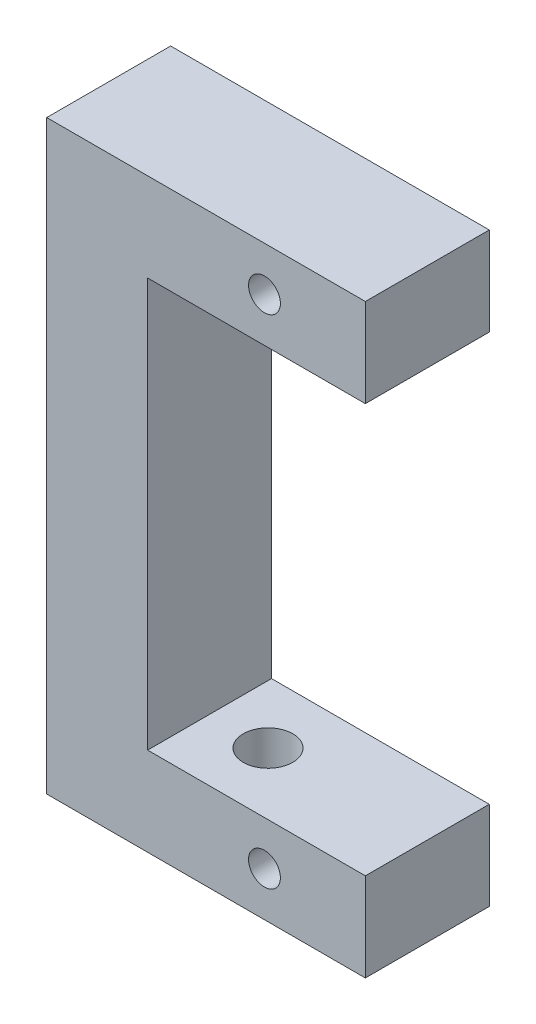
SolidWorks part; units mm, degrees
ref_plane "Front Plane" through (0, 0, 0) normal (0, 0, 1) x (1, 0, 0)
ref_plane "Top Plane" through (0, 0, 0) normal (0, 1, 0) x (1, 0, 0)
ref_plane "Right Plane" through (0, 0, 0) normal (1, 0, 0) x (0, 0, -1)
sketch "Schizzo1" plane through (0, 0, 0) normal (0, 0, 1) x (1, 0, 0)
  line L0 (8.3, 11.55) -> (-4, 11.55)
  line L5 (-4, 11.55) -> (-4, -11.55)
  line L6 (-4, -11.55) -> (8.3, -11.55)
  line L7 (8.3, -11.55) -> (8.3, -16.55)
  line L8 (8.3, -16.55) -> (-9.7, -16.55)
  line L9 (-9.7, -16.55) -> (-9.7, 16.55)
  line L10 (-9.7, 16.55) -> (8.3, 16.55)
  line L11 (8.3, 16.55) -> (8.3, 11.55)
  point P2 (-4, 0)
  dimension "D1" = 23.1
  dimension "D2" = 12.3
  dimension "D3" = 18
  dimension "D4" = 5
  dimension "D5" = 4
extrude "Estrusione-Estrusione1" add sketch "Schizzo1" along normal blind 7
sketch "Schizzo2" plane through (0, 0, 7) normal (0, 0, 1) x (1, 0, 0)
  line L0 (-4, 11.55) -> (8.3, 11.55) construction
  line L1 (0, 0) -> (14.3967, 0) construction
  line L2 (8.3, 11.55) -> (8.3, 16.55) construction
  circle A0 centre (2.6, 14.05) radius 0.9
  circle A1 centre (2.6, -14.05) radius 0.9
  point P5 (2.15, 11.55)
  point P10 (0, 0)
  dimension "D1" = 1.8
  dimension "D2" = 2.5
  dimension "D3" = 5.7
extrude "Taglio-Estrusione1" cut sketch "Schizzo2" against normal through all
sketch "Schizzo3" plane through (0, -16.55, 0) normal (0, -1, 0) x (1, 0, 0)
  line L0 (-9.7, 0) -> (8.3, 0) construction
  line L1 (-9.7, 7) -> (-9.7, 0) construction
  circle A0 centre (-0.7, 3.5) radius 1.4
  point P4 (-0.7, 0)
  point P7 (-9.7, 3.5)
  dimension "D1" = 2.8
extrude "Taglio-Estrusione2" cut sketch "Schizzo3" against normal up to next
